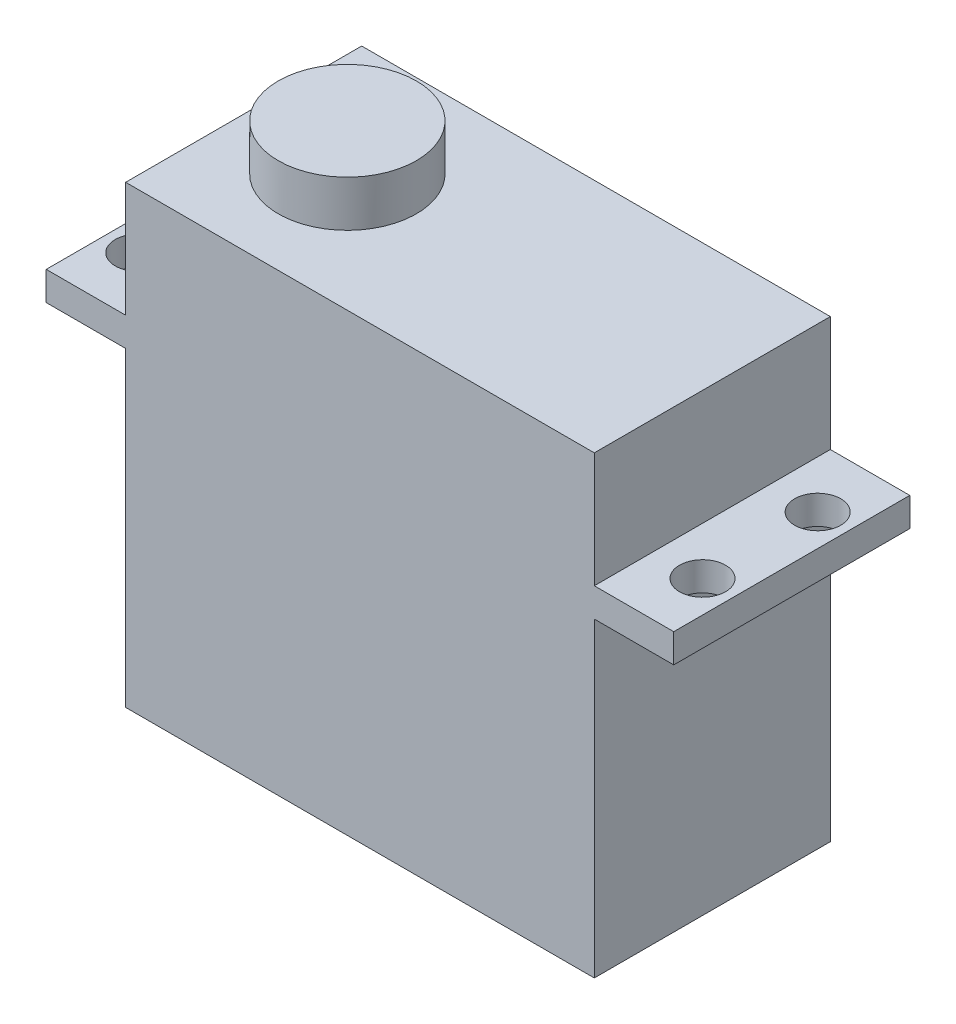
SolidWorks part; units mm, degrees
ref_plane "Front Plane" through (0, 0, 0) normal (0, 0, 1) x (1, 0, 0)
ref_plane "Top Plane" through (0, 0, 0) normal (0, 1, 0) x (1, 0, 0)
ref_plane "Right Plane" through (0, 0, 0) normal (1, 0, 0) x (0, 0, -1)
sketch "Sketch2" plane through (0, 0, 0) normal (0, 1, 0) x (1, 0, 0)
  line L1 (-20.35, -10.25) -> (20.35, -10.25)
  line L2 (-20.35, -10.25) -> (-20.35, 10.25)
  line L3 (-20.35, 10.25) -> (20.35, 10.25)
  line L4 (20.35, -10.25) -> (20.35, 10.25)
  line L5 (-20.35, -10.25) -> (20.35, 10.25) construction
  line L6 (-20.35, 10.25) -> (20.35, -10.25) construction
  point P0 (0, 0)
  dimension "D1" = 40.7
  dimension "D2" = 20.5
extrude "Boss-Extrude1" add sketch "Sketch2" along normal blind 27
sketch "Sketch3" plane through (0, 27, 0) normal (0, 1, 0) x (1, 0, 0)
  line L0 (-27.25, 0) -> (-24.5, 0) construction
  line L1 (-27.25, -10.25) -> (27.25, -10.25)
  line L2 (-27.25, -10.25) -> (-27.25, 10.25)
  line L3 (-27.25, 10.25) -> (27.25, 10.25)
  line L4 (27.25, -10.25) -> (27.25, 10.25)
  line L5 (-27.25, -10.25) -> (27.25, 10.25) construction
  line L6 (-27.25, 10.25) -> (27.25, -10.25) construction
  line L7 (-24.5, 0) -> (-24.5, 5) construction
  line L8 (0, 10.25) -> (0, -10.25) construction
  circle A0 centre (-24.5, 5) radius 2
  circle A1 centre (-24.5, -5) radius 2
  circle A2 centre (24.5, -5) radius 2
  circle A3 centre (24.5, 5) radius 2
  point P0 (0, 0)
  dimension "D5" = 4
  dimension "D1" = 20.5
  dimension "D2" = 54.5
  dimension "D3" = 2.75
  dimension "D4" = 5
extrude "Boss-Extrude2" add sketch "Sketch3" along normal blind 2.5
sketch "Sketch4" plane through (0, 29.5, 0) normal (0, 1, 0) x (1, 0, 0)
  line L1 (20.35, 10.25) -> (-20.35, 10.25)
  line L2 (20.35, 10.25) -> (20.35, -10.25)
  line L3 (20.35, -10.25) -> (-20.35, -10.25)
  line L4 (-20.35, 10.25) -> (-20.35, -10.25)
  line L5 (20.35, 10.25) -> (-20.35, -10.25) construction
  line L6 (20.35, -10.25) -> (-20.35, 10.25) construction
  point P0 (0, 0)
  dimension "D1" = 20.5
  dimension "D2" = 40.7
extrude "Boss-Extrude3" add sketch "Sketch4" along normal blind 10
sketch "Sketch5" plane through (0, 39.5, 0) normal (0, 1, 0) x (1, 0, 0)
  line L0 (-20.35, 0) -> (-11.35, 0) construction
  line L1 (-20.35, 10.25) -> (-20.35, -10.25) construction
  circle A0 centre (-11.35, 0) radius 6
  dimension "D2" = 12
  dimension "D1" = 9
extrude "Boss-Extrude4" add sketch "Sketch5" along normal blind 4
